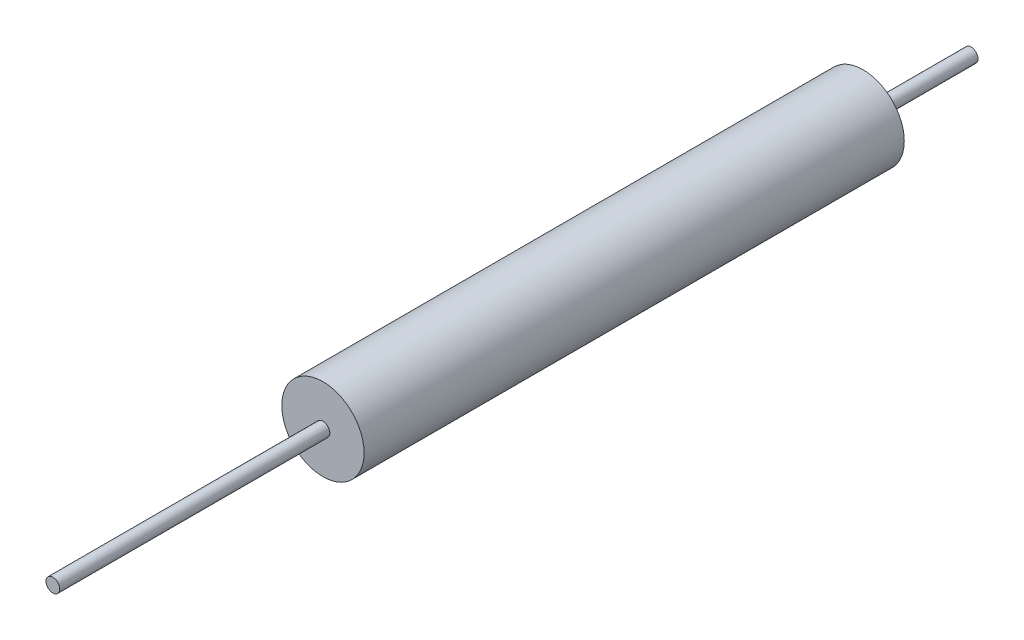
SolidWorks part; units mm, degrees
ref_plane "Alzado" through (0, 0, 0) normal (0, 0, 1) x (1, 0, 0)
ref_plane "Planta" through (0, 0, 0) normal (0, 1, 0) x (1, 0, 0)
ref_plane "Vista lateral" through (0, 0, 0) normal (1, 0, 0) x (0, 0, -1)
sketch "Croquis1" plane through (0, 0, 0) normal (0, 0, 1) x (1, 0, 0)
  circle A0 centre (0, 0) radius 19.05
  dimension "D1" = 38.1
extrude "Saliente-Extruir1" add sketch "Croquis1" along normal blind 250
sketch "Croquis2" plane through (0, 0, 0) normal (0, 0, -1) x (-1, 0, 0)
  circle A0 centre (0, 0) radius 3.175
  dimension "D1" = 6.35
extrude "Saliente-Extruir2" add sketch "Croquis2" along normal blind 50
sketch "Croquis3" plane through (0, 0, 250) normal (0, 0, 1) x (1, 0, 0)
  circle A0 centre (0, 0) radius 3.175
  dimension "D1" = 6.35
extrude "Saliente-Extruir3" add sketch "Croquis3" along normal blind 125
